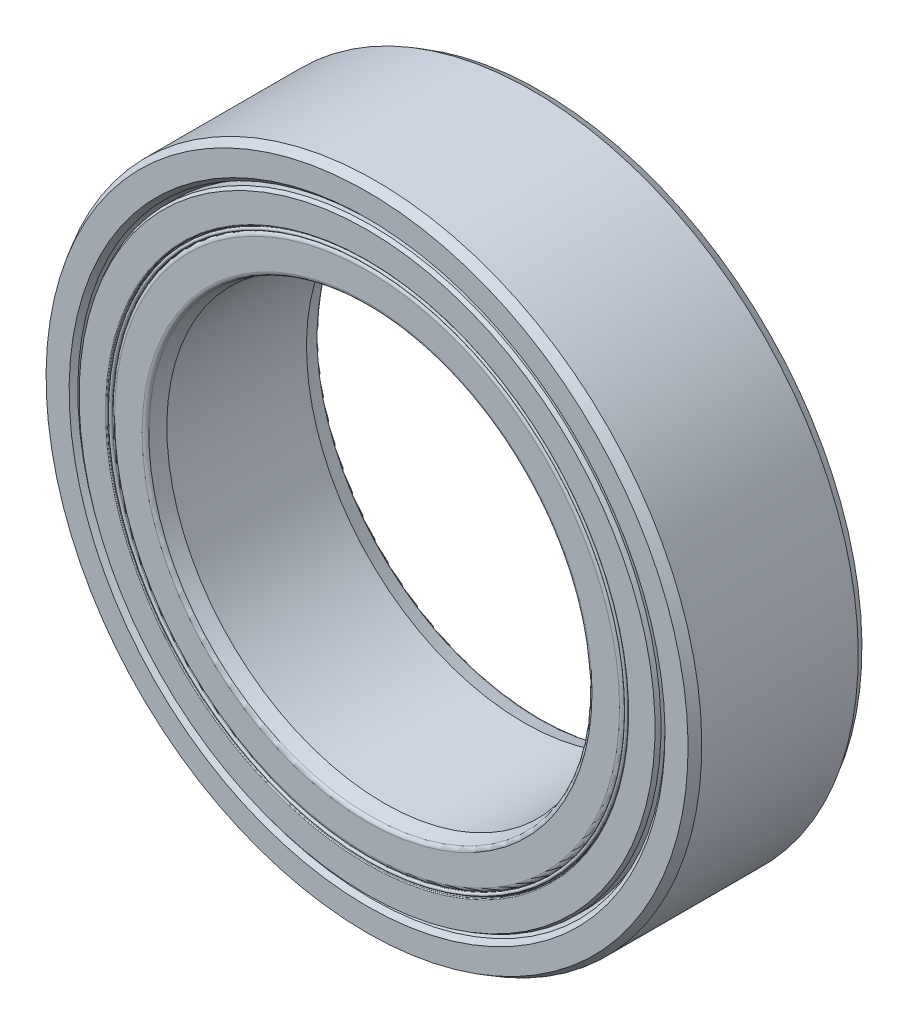
SolidWorks part; units mm, degrees
ref_plane "Front Plane" through (0, 0, 0) normal (0, 0, 1) x (1, 0, 0)
ref_plane "Top Plane" through (0, 0, 0) normal (0, 1, 0) x (1, 0, 0)
ref_plane "Right Plane" through (0, 0, 0) normal (1, 0, 0) x (0, 0, -1)
sketch "Sketch1" plane through (0, 0, 0) normal (0, 0, 1) x (1, 0, 0)
  line L0 (-7.5, 0) -> (7.5, 0) construction
  line L1 (-5, 0) -> (5, 0) construction
  circle A0 centre (0, 0) radius 5 construction
  circle A1 centre (0, 0) radius 7.5 construction
  point P3 (0, 0)
  point P6 (0, 0)
  point P7 (0, -5)
  point P11 (0, -7.5)
  point P12 (0, 5)
  point P13 (0, 7.5)
  dimension "OD" = 15
  dimension "ID" = 10
sketch "Sketch2" plane through (0, 0, 0) normal (1, 0, 0) x (0, 0, -1)
  line L0 (-2, 7.5) -> (2, 7.5) construction
  line L1 (0, 7.5) -> (0, -7.5) construction
  line L2 (1.8, 7.5) -> (-1.8, 7.5)
  line L3 (-1.8, 7.5) -> (-2, 7.3845)
  line L4 (-2, 7.3845) -> (-2, 6.854)
  line L5 (-1.683, 6.675) -> (-0.8537, 6.675)
  line L6 (1.683, 6.675) -> (0.8537, 6.675)
  line L7 (2, 7.3845) -> (2, 6.854)
  line L8 (1.8, 7.5) -> (2, 7.3845)
  line L9 (-0.8537, 6.675) -> (-0.8537, 6.95) construction
  line L10 (-0.8537, 6.95) -> (-0.8537, 7.225) construction
  line L11 (0, 7.5) -> (0, -7.5) construction
  line L12 (-2, 0) -> (2, 0) construction
  line L13 (2, 5) -> (-2, 5) construction
  line L14 (-2, 5) -> (-2, -5) construction
  line L15 (-2, -5) -> (2, -5) construction
  line L16 (2, 7.5) -> (2, -7.5) construction
  line L17 (-0.8537, 7.225) -> (-0.8537, 7.5) construction
  line L18 (-0.8537, 7.225) -> (0, 7.225) construction
  line L20 (-1.683, 6.675) -> (-1.9, 6.754)
  line L21 (-1.9, 6.754) -> (-2, 6.854)
  line L26 (1.9, 6.754) -> (2, 6.854)
  line L27 (1.683, 6.675) -> (1.9, 6.754)
  arc A0 (-0.8537, 6.675) -> (0.8537, 6.675) centre (0, 6.2875) cw
  circle A1 centre (0, 6.2875) radius 0.9375 construction
  point P17 (0, 0)
  point P21 (0, 7.5)
  point P30 (0, -5)
  dimension "Approx. Ball Dia." = 1.875
  dimension "Width" = 4
  dimension "For Shaft Diameter" = 10
  dimension "For Housing ID" = 15
  dimension "D4" = 13.35
  dimension "D2" = 20
  dimension "D5" = 45
  dimension "D1" = 30
  dimension "D6" = 0.2
  dimension "D7" = 0.1
sketch "Sketch3" plane through (0, 0, 0) normal (1, 0, 0) x (0, 0, -1)
  line L14 (-1.683, 6.675) -> (-1.9, 6.754) construction
  line L15 (-1.9, 6.754) -> (-2, 6.854) construction
  line L16 (-2, 7.3845) -> (-2, 6.854) construction
  line L17 (-1.8, 7.5) -> (-2, 7.3845) construction
  line L18 (1.8, 7.5) -> (-1.8, 7.5) construction
  line L19 (1.8, 7.5) -> (2, 7.3845) construction
  line L20 (2, 7.3845) -> (2, 6.854) construction
  line L21 (1.9, 6.754) -> (2, 6.854) construction
  line L22 (1.683, 6.675) -> (1.9, 6.754) construction
  line L23 (1.683, 6.675) -> (0.8537, 6.675) construction
  line L24 (-1.683, 6.675) -> (-0.8537, 6.675) construction
  line L25 (-1.683, 6.675) -> (-1.9, 6.754)
  line L26 (-1.9, 6.754) -> (-2, 6.854)
  line L27 (-2, 7.3845) -> (-2, 6.854)
  line L28 (-1.8, 7.5) -> (-2, 7.3845)
  line L29 (1.8, 7.5) -> (-1.8, 7.5)
  line L30 (1.8, 7.5) -> (2, 7.3845)
  line L31 (2, 7.3845) -> (2, 6.854)
  line L32 (1.9, 6.754) -> (2, 6.854)
  line L33 (1.683, 6.675) -> (1.9, 6.754)
  line L34 (1.683, 6.675) -> (0.8537, 6.675)
  line L35 (-1.683, 6.675) -> (-0.8537, 6.675)
  arc A2 (0.8537, 6.675) -> (-0.8537, 6.675) centre (0, 6.2875) ccw construction
  arc A3 (0.8537, 6.675) -> (-0.8537, 6.675) centre (0, 6.2875) ccw
revolve "Revolve1" add sketch "Sketch3" angle 360 about L12
sketch "Sketch4" plane through (0, 0, 0) normal (1, 0, 0) x (0, 0, -1)
  line L0 (0, 7.5) -> (0, -7.5) construction
  line L1 (0, 7.5) -> (0, -7.5) construction
  line L2 (-1.6063, 5) -> (-1.9329, 5.0875)
  line L3 (-2, 5.175) -> (-2, 5.8094)
  line L4 (2, -7.3845) -> (2, 7.3845) construction
  line L5 (-1.9094, 5.9) -> (-0.8537, 5.9)
  line L6 (-1.6063, 5) -> (1.6063, 5)
  line L7 (2, 7.3845) -> (2, 6.854) construction
  line L8 (1.6063, 5) -> (1.9329, 5.0875)
  line L9 (0, 7.225) -> (0, 5) construction
  line L10 (2, 5.175) -> (2, 5.8094)
  line L11 (1.9094, 5.9) -> (0.8537, 5.9)
  line L12 (1.6063, 5) -> (1.6063, 5.0875) construction
  line L13 (1.6063, 5.0875) -> (1.6063, 5.175) construction
  line L14 (1.6063, 5.175) -> (1.6063, 5.2625) construction
  line L15 (1.6063, 5.2625) -> (1.6063, 5.35) construction
  circle A0 centre (0, 6.2875) radius 0.9375 construction
  arc A1 (0.8537, 5.9) -> (-0.8537, 5.9) centre (0, 6.2875) cw
  arc A2 (2, 5.8094) -> (1.9094, 5.9) centre (1.9094, 5.8094) ccw
  arc A3 (-2, 5.8094) -> (-1.9094, 5.9) centre (-1.9094, 5.8094) cw
  arc A4 (1.9329, 5.0875) -> (2, 5.175) centre (1.9094, 5.175) ccw
  arc A5 (-1.9329, 5.0875) -> (-2, 5.175) centre (-1.9094, 5.175) cw
  point P14 (2, 5.1055)
  point P36 (0, 5.35)
  dimension "D1" = 15
revolve "Revolve2" add sketch "Sketch4" angle 360 about L12
sketch "Sketch5" plane through (0, 0, 0) normal (1, 0, 0) x (0, 0, -1)
  line L0 (-0.9375, 6.2875) -> (0.9375, 6.2875)
  arc A2 (-0.9375, 6.2875) -> (0.9375, 6.2875) centre (0, 6.2875) cw
  arc A3 (0.8537, 6.675) -> (-0.8537, 6.675) centre (0, 6.2875) ccw construction
revolve "Revolve3" add sketch "Sketch5" angle 360 about L0
pattern_circular "CirPattern1" count 14 over 360 about axis through (0, 0, 0) along (0, 0, 1) of bodies 104
sketch "Sketch6" plane through (0, 0, 0) normal (1, 0, 0) x (0, 0, -1)
  line L1 (-1.9134, 6.675) -> (-0.9375, 6.675)
  line L2 (-2, 6.625) -> (-2, 6.02)
  line L3 (-1.98, 6) -> (-0.9375, 6)
  line L4 (-0.9375, 6.675) -> (-0.9375, 6)
  line L5 (-2, 5.175) -> (-2, 5.8094) construction
  line L6 (-1.8, 7.5) -> (-2, 7.3845) construction
  line L7 (0, 7.5) -> (0, 5) construction
  line L8 (1.98, 6) -> (0.9375, 6)
  line L9 (0.9375, 6.675) -> (0.9375, 6)
  line L10 (1.9134, 6.675) -> (0.9375, 6.675)
  line L11 (2, 6.625) -> (2, 6.02)
  line L13 (-1.9094, 5.9) -> (-0.8537, 5.9) construction
  line L14 (-2, 6.625) -> (-1.9134, 6.675)
  line L15 (-1.683, 6.675) -> (-0.8537, 6.675) construction
  line L16 (2, 6.625) -> (1.9134, 6.675)
  arc A0 (-2, 6.02) -> (-1.98, 6) centre (-1.98, 6.02) ccw
  circle A1 centre (0, 6.2875) radius 0.9375 construction
  arc A2 (2, 6.02) -> (1.98, 6) centre (1.98, 6.02) cw
  point P26 (-2, 6)
  dimension "D3" = 0.02
  dimension "D1" = 0.1
  dimension "D2" = 0.05
revolve "Revolve4" add sketch "Sketch6" angle 360 about L12
sketch "Sketch7" plane through (0, 0, 0) normal (1, 0, 0) x (0, 0, -1)
  line L3 (-0.9375, 6) -> (-1.9147, 6)
  line L4 (-1.98, 6) -> (-0.9375, 6) construction
  line L7 (0, 5.35) -> (0, 5) construction
  line L8 (0, 7.5) -> (0, -7.5) construction
  line L21 (-1.9147, 6) -> (-1.9393, 5.9957)
  line L22 (-1.9375, 5.975) -> (-1.9625, 5.975)
  line L23 (-1.9625, 5.9) -> (-0.9375, 5.9)
  line L24 (-0.9375, 5.9) -> (-0.9375, 6)
  line L25 (-1.9094, 5.9) -> (-0.8537, 5.9) construction
  line L26 (-2, 6.02) -> (-2, 5.9) construction
  line L27 (-2, 5.9) -> (-1.9625, 5.9) construction
  line L28 (-1.9147, 6) -> (-1.9147, 5.975) construction
  line L29 (-1.9147, 5.975) -> (-1.9147, 5.95) construction
  line L30 (-1.9147, 5.95) -> (-1.9147, 5.925) construction
  line L31 (-1.9147, 5.925) -> (-1.9147, 5.9) construction
  circle A2 centre (0, 6.2875) radius 0.9375 construction
  arc A9 (-1.9393, 5.9957) -> (-1.9375, 5.975) centre (-1.9375, 5.9854) ccw
  arc A10 (-1.9625, 5.975) -> (-1.9625, 5.9) centre (-1.9625, 5.9375) ccw
  dimension "D1" = 0.025
  dimension "D2" = 10
revolve "Revolve5" add sketch "Sketch7" angle 360 about L12
equation "\"D4@Sketch2\"=\"OD@Sketch1\"*.89"
equation "\"D1@Sketch6\"=(\"OD@Sketch1\"-\"ID@Sketch1\")*.02"
equation "\"D2@Sketch6\"=\"D1@Sketch6\"*.5"
equation "\"D3@Sketch6\"=\"D1@Sketch6\"*.2"
equation "\"D6@Sketch2\"=\"Width@Sketch2\"*.05"
equation "\"D7@Sketch2\"=\"D6@Sketch2\"*.5"
equation "\"D1@CirPattern1\" =  ( pi * \"OD@Sketch1\" )  * .5625 / \"Approx. Ball Dia.@Sketch2\""
equation "\"Approx. Ball Dia.@Sketch2\"=(\"OD@Sketch1\"-\"ID@Sketch1\")*.5*.75"
